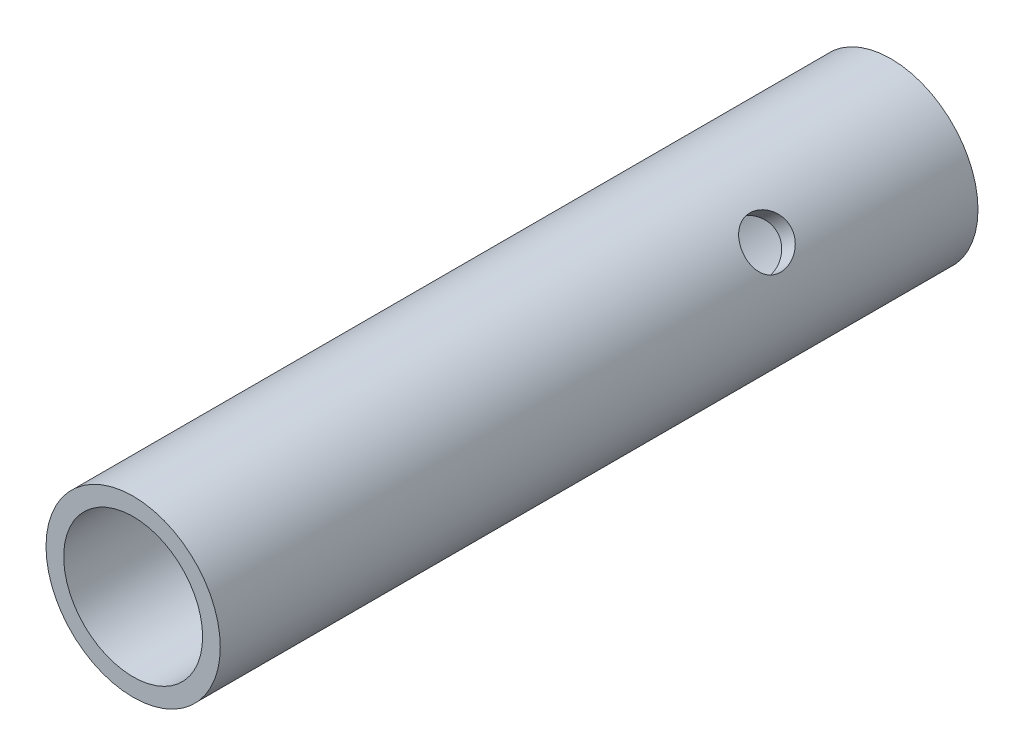
SolidWorks part; units mm, degrees
ref_plane "Front Plane" through (0, 0, 0) normal (0, 0, 1) x (1, 0, 0)
ref_plane "Top Plane" through (0, 0, 0) normal (0, 1, 0) x (1, 0, 0)
ref_plane "Right Plane" through (0, 0, 0) normal (1, 0, 0) x (0, 0, -1)
sketch "Sketch1" plane through (0, 0, 0) normal (0, 0, 1) x (1, 0, 0)
  circle A0 centre (0, 0) radius 17.526 construction
  circle A1 centre (0, 0) radius 13.97 construction
  point P3 (-17.526, 0)
  point P4 (17.526, 0)
  point P6 (-13.97, 0)
  point P7 (13.97, 0)
  dimension "OD" = 35.052
  dimension "Wall" = 3.556
  dimension "ID" = 27.94
sketch "Sketch2" plane through (0, 0, 0) normal (1, 0, 0) x (0, 0, -1)
  line L0 (76.2, 0) -> (-76.2, 0) construction
  line L2 (0, 17.526) -> (0, -17.526) construction
  line L3 (0, 17.526) -> (0, -17.526) construction
  line L4 (76.2, 17.526) -> (-76.2, 17.526) construction
  line L5 (76.2, -17.526) -> (-76.2, -17.526) construction
  line L6 (-76.2, -17.526) -> (-76.2, 17.526) construction
  line L7 (76.2, -17.526) -> (76.2, 17.526) construction
  line L8 (-41.148, -17.526) -> (-41.148, 17.526) construction
  line L9 (41.148, -17.526) -> (41.148, 17.526) construction
  point P3 (0, 0)
  point P9 (0, 17.526)
  point P11 (0, -17.526)
  point P13 (-76.2, 0)
  point P14 (76.2, 17.526)
  point P15 (-76.2, -17.526)
  point P16 (-76.2, 17.526)
  point P17 (-76.2, 0)
  point P18 (76.2, -17.526)
  point P19 (76.2, 0)
  point P22 (-41.148, 0)
  point P25 (41.148, 0)
  point P26 (-41.148, -17.526)
  point P27 (-41.148, 17.526)
  point P28 (41.148, 17.526)
  point P29 (41.148, -17.526)
  dimension "Length" = 152.4
  dimension "D1" = 35.052
sketch "Sketch3" plane through (0, 0, 0) normal (0, 0, 1) x (1, 0, 0)
  circle A0 centre (0, 0) radius 17.526 construction
  circle A1 centre (0, 0) radius 13.97 construction
  circle A2 centre (0, 0) radius 17.526
  circle A3 centre (0, 0) radius 13.97
extrude "Boss-Extrude1" add sketch "Sketch3" along normal mid plane 152.4
ref_plane "Plane1" through (0, 22.225, 0) normal (0, 1, 0) x (1, 0, 0)
ref_plane "Plane2" through (22.225, 0, 0) normal (1, 0, 0) x (0, 0, -1)
ref_plane "Plane3" through (-33.8, -28.868, -158.75) normal (-0.7604, -0.6494, 0) x (-0.6494, 0.7604, 0)
sketch "Sketch5" plane through (-33.8, -28.868, -158.75) normal (-0.7604, -0.6494, 0) x (-0.6494, 0.7604, 0)
  circle A0 centre (0, -120.65) radius 4.7625
  dimension "D1" = 9.525
extrude "Cut-Extrude1" cut sketch "Sketch5" against normal through all
equation "\"D1@Sketch2\"=\"OD@Sketch1\""
equation "\"D1@Boss-Extrude1\"=\"Length@Sketch2\""
equation "\"Wall@Sketch1\"=0.28/2"
